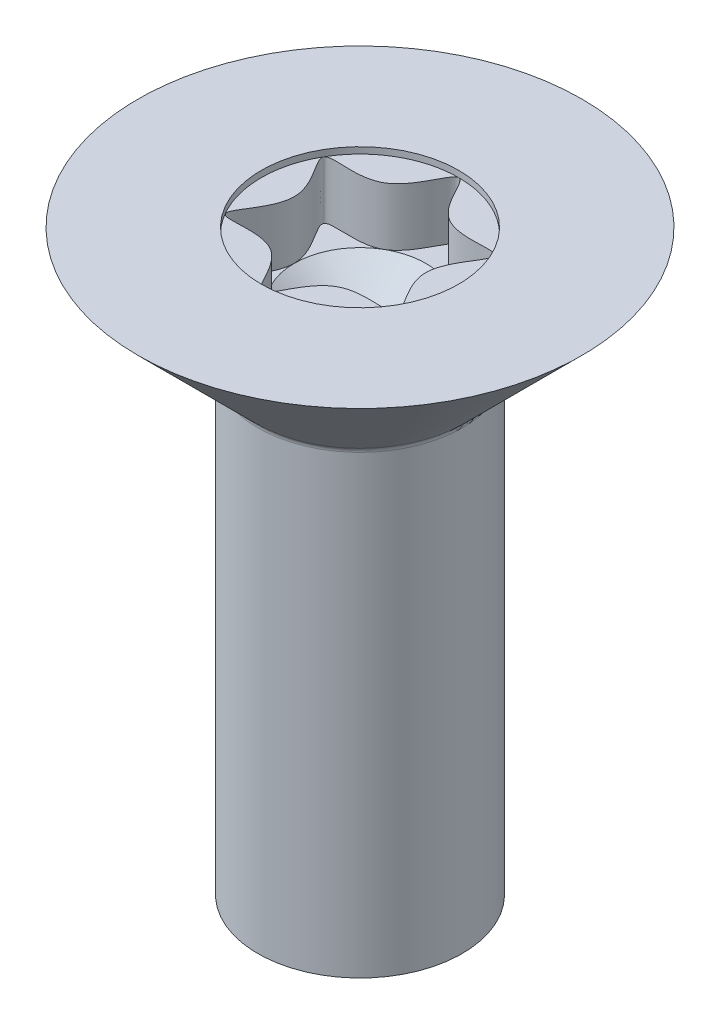
SolidWorks part; units mm, degrees
ref_plane "Front" through (0, 0, 0) normal (0, 0, 1) x (1, 0, 0)
ref_plane "Top" through (0, 0, 0) normal (0, 1, 0) x (1, 0, 0)
ref_plane "Right" through (0, 0, 0) normal (1, 0, 0) x (0, 0, -1)
sketch "Sketch1" plane through (0, 0, 0) normal (0, 0, 1) x (1, 0, 0)
  line L0 (0, 0) -> (0, 8.8882) construction
  line L1 (0, 8.2) -> (3.15, 8.2)
  line L2 (1.45, 0) -> (1.45, 6.5)
  line L3 (1.45, 6.5) -> (2.55, 6.5) construction
  line L4 (2.55, 6.5) -> (2.55, 5.4) construction
  line L5 (1.45, 0) -> (0, 0)
  line L6 (0, 0) -> (0, 8.2)
  line L7 (3.15, 8.2) -> (1.45, 6.5)
  dimension "head_dia" = 6.3
  dimension "head_ht" = 1.7
  dimension "length" = 8.2
  dimension "D1" = 45
  dimension "pitch" = 1.1
  dimension "thread_gap" = 1.1
revolve "Body-Revolve" add sketch "Sketch1" angle 360 about L0
cosmetic thread "ThreadCosmetic" [suppressed] parameters "D1"=5.4, "D2"=1.7092
sketch "Sketch2" plane through (0, 8.2, 0) normal (0, 1, 0) x (-1, 0, 0)
  line L0 (0, 0) -> (0, -1.54)
  line L1 (0, 0) -> (-0.7, -1.2124)
  circle A0 centre (0, 0) radius 1.4
  circle A1 centre (0, 0) radius 0.9333
  spline S0 degree 3 poles (0.302, -0.523) (0, -1.8385) (-0.302, -0.523) (-1.5922, -0.9193) (-0.6039, 0) (-1.5922, 0.9193) (-0.302, 0.523) (0, 1.8385) (0.302, 0.523) (1.5922, 0.9193) (0.6039, 0) (1.5922, -0.9193) (0.302, -0.523) (0, -1.8385) (-0.302, -0.523) knots -0.25 -0.166667 -0.083333 0 0.083333 0.166667 0.25 0.333333 0.416667 0.5 0.583333 0.666667 0.75 0.833333 0.916667 1 1.083333 1.166667 1.25 only from (0, -1.4) to (0, -1.4)
  point P4 (0, -1.4)
  point P7 (-0.4667, -0.8083)
  point P10 (-1.2124, -0.7)
  point P11 (-1.2124, 0.7)
  point P12 (0, 1.4)
  point P13 (1.2124, 0.7)
  point P14 (1.2124, -0.7)
  point P15 (-0.9333, 0)
  point P16 (-0.4667, 0.8083)
  point P17 (0.4667, 0.8083)
  point P18 (0.9333, 0)
  point P19 (0.4667, -0.8083)
  dimension "socket_dia" = 2.8
  dimension "D1" = 1.8667
  dimension "D2" = 30
  dimension "D3" = 1.54
extrude "Recess-Cut-Extrude1" cut sketch "Sketch2" against normal blind 0.91 contours S0
sketch "Sketch3" plane through (0, 8.2, 0) normal (0, 1, 0) x (-1, 0, 0)
  circle A0 centre (0, 0) radius 1.4
  dimension "D1" = 2.8
extrude "Recess-Cut-Extrude2" cut sketch "Sketch3" against normal blind 0.091
sketch "Sketch4" plane through (0, 0, 0) normal (0, 0, 1) x (1, 0, 0)
  line L0 (0, 7.29) -> (0.9333, 7.29)
  line L1 (1.2177, 7.29) -> (-1.2177, 7.29) construction
  line L2 (0.9333, 7.29) -> (0, 6.67)
  line L3 (0, 0) -> (0, 8.8882) construction
  line L4 (0, 6.67) -> (0, 7.29)
  line L5 (1.4, 8.2) -> (-1.4, 8.2) construction
  dimension "D1" = 1.53
  dimension "D2" = 0.9333
revolve "Drill-Cut-Revolve" cut sketch "Sketch4" angle 360 about axis through (0, 0, 0) along (0, 1, 0)
fillet "Fillet1" radius 0.1 1 edges at (0, 6.5, -1.45)
sketch "Sketch5" plane through (0, 0, 0) normal (0, 0, 1) x (1, 0, 0)
  line L0 (1.45, 5.4) -> (1.45, 4.7125)
  line L1 (1.45, 0) -> (1.45, 6.4586) construction
  line L2 (1.45, 4.7125) -> (0.8546, 5.0563)
  line L3 (0.8546, 5.0563) -> (1.45, 5.4)
  line L4 (0, 0) -> (0, 8.8882) construction
  line L5 (-1.45, 0) -> (1.45, 0) construction
  dimension "D1" = 0.8546
  dimension "D2" = 5.4
revolve "ThreadSchematic" [suppressed] cut sketch "Sketch5" angle 360 about axis through (0, 0, 0) along (0, 1, 0)
pattern_linear "ThdSchPat" [suppressed] count 5 spacing 1.1 along (0, 1, 0)
sketch "Sketch6" plane through (0, 0, 0) normal (0, 0, 1) x (1, 0, 0)
  line L0 (0.01, 0) -> (1.45, 0)
  line L1 (-1.45, 0) -> (1.45, 0) construction
  line L2 (1.45, 0) -> (1.45, 2.6)
  line L4 (1.45, 2.6) -> (0.01, 0)
  line L5 (0, 0) -> (0, 8.8882) construction
  dimension "D1" = 1.45
  dimension "end_lengthC" = 2.6
  dimension "D2" = 0.01
revolve "TypeC" [suppressed] cut sketch "Sketch6" angle 360 about axis through (0, 0, 0) along (0, 1, 0)
sketch "Sketch7" plane through (0, 0, 0) normal (0, 0, 1) x (1, 0, 0)
  line L0 (1.2293, 0) -> (1.45, 0)
  line L1 (0, 0) -> (0, 8.8882) construction
  line L2 (1.45, 0) -> (1.45, 2.1)
  line L4 (1.45, 2.1) -> (1.2293, 0)
  line L5 (-1.45, 0) -> (1.45, 0) construction
  dimension "end_lengthF" = 2.1
  dimension "D1" = 6
  dimension "D2" = 1.45
revolve "TypeF" [suppressed] cut sketch "Sketch7" angle 360 about axis through (0, 0, 0) along (0, 1, 0)
sketch "Sketch8" plane through (0, 0, 0) normal (0, 0, 1) x (1, 0, 0)
  line L0 (1.45, -0.09) -> (1.45, 2)
  line L2 (1.45, 2) -> (0.1163, 0.0456)
  line L3 (0.03, 0) -> (0.03, -0.09)
  line L4 (0.03, -0.09) -> (1.45, -0.09)
  line L5 (0, 0) -> (0, 8.8882) construction
  line L9 (-1.45, 0) -> (1.45, 0) construction
  arc A0 (0.1163, 0.0456) -> (0.03, 0) centre (0.03, 0.1045) cw
  dimension "D4" = 0.1045
  dimension "D1" = 0.09
  dimension "D2" = 0.03
  dimension "D3" = 1.45
  dimension "end_lengthR" = 2.09
revolve "TypeR" [suppressed] cut sketch "Sketch8" angle 360 about axis through (0, 0, 0) along (0, 1, 0)
equation "\"thread_gap@Sketch1\" = \"pitch@Sketch1\""
equation "\"D1@ThreadCosmetic\" = \"length@Sketch1\" - \"head_ht@Sketch1\" - \"thread_gap@Sketch1\""
equation "\"D2@ThreadCosmetic\" = \"head_dia@Sketch1\" - \"head_ht@Sketch1\" * 2 - 1.0825 * \"pitch@Sketch1\""
equation "\"D1@Sketch2\" = \"socket_dia@Sketch2\" / 1.5"
equation "\"D3@Sketch2\" = \"socket_dia@Sketch2\" / 2 * 1.1"
equation "\"D1@Sketch3\" = \"socket_dia@Sketch2\""
equation "\"D1@Recess-Cut-Extrude2\" = 0.1 * \"socket-dep@Recess-Cut-Extrude1\""
equation "\"D1@Sketch4\" = 0.9*\"head_ht@Sketch1\""
equation "\"D2@Sketch4\" = \"D1@Sketch2\" / 2"
equation "\"D1@Sketch5\" = \"D2@ThreadCosmetic\" / 2"
equation "\"D2@Sketch5\" = \"D1@ThreadCosmetic\""
equation "\"D3@ThdSchPat\" = \"pitch@Sketch1\""
equation "\"D1@ThdSchPat\" = \"D1@ThreadCosmetic\" / \"D3@ThdSchPat\""
equation "\"D1@Sketch6\" = \"head_dia@Sketch1\" / 2 - \"head_ht@Sketch1\""
equation "\"D2@Sketch7\" = \"head_dia@Sketch1\" / 2 - \"head_ht@Sketch1\""
equation "\"D3@Sketch8\" = \"head_dia@Sketch1\" * 0.5 - \"head_ht@Sketch1\""
equation "\"D4@Sketch8\" = \"end_lengthR@Sketch8\" / 20"
